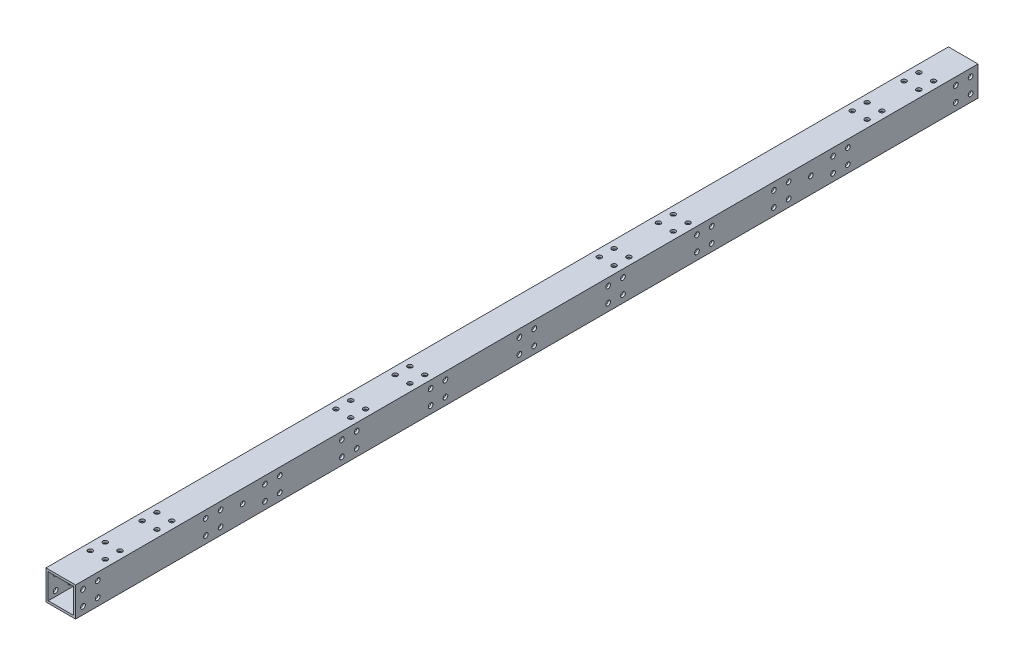
SolidWorks part; units mm, degrees
ref_plane "前视基准面" through (0, 0, 0) normal (0, 0, 1) x (1, 0, 0)
ref_plane "上视基准面" through (0, 0, 0) normal (0, 1, 0) x (1, 0, 0)
ref_plane "右视基准面" through (0, 0, 0) normal (1, 0, 0) x (0, 0, -1)
other "Configuration Table"
sketch "草图1" plane through (0, 0, 0) normal (0, 0, 1) x (1, 0, 0)
  line L10 (0, 0) -> (20, 0)
  line L11 (0, 0) -> (0, -20)
  line L12 (0, -20) -> (20, -20)
  line L13 (20, 0) -> (20, -20)
  dimension "D1" = 20
  dimension "D2" = 20
extrude "拉伸-薄壁1" add sketch "草图1" along normal blind 610 thin
sketch "草图2" plane through (0, 0, 0) normal (0, 1, 0) x (1, 0, 0)
  line L0 (20, -236) -> (0, -236) construction
  line L1 (20, -610) -> (20, 0) construction
  line L2 (0, -610) -> (0, 0) construction
  line L3 (20, 0) -> (0, 0) construction
  line L4 (0, -305) -> (20, -305) construction
  line L5 (10, -305) -> (10, -236) construction
  line L6 (20, -374) -> (0, -374) construction
  line L7 (0, -30) -> (20, -30) construction
  line L8 (0, -580) -> (20, -580) construction
  line L9 (0, -65) -> (20, -65) construction
  line L10 (0, -216) -> (20, -216) construction
  line L11 (20, -196) -> (0, -196) construction
  line L12 (0, -394) -> (20, -394) construction
  line L13 (20, -414) -> (0, -414) construction
  circle A0 centre (5, -231) radius 1.575
  circle A1 centre (15, -231) radius 1.575
  circle A2 centre (15, -241) radius 1.575
  circle A3 centre (5, -241) radius 1.575
  circle A4 centre (5, -369) radius 1.575
  circle A5 centre (15, -369) radius 1.575
  circle A6 centre (15, -379) radius 1.575
  circle A7 centre (5, -379) radius 1.575
  circle A8 centre (5, -25) radius 1.575
  circle A9 centre (15, -25) radius 1.575
  circle A10 centre (15, -35) radius 1.575
  circle A11 centre (5, -35) radius 1.575
  circle A12 centre (5, -575) radius 1.575
  circle A13 centre (15, -575) radius 1.575
  circle A14 centre (15, -585) radius 1.575
  circle A15 centre (5, -585) radius 1.575
  circle A16 centre (5, -60) radius 1.575
  circle A17 centre (15, -60) radius 1.575
  circle A18 centre (15, -70) radius 1.575
  circle A19 centre (5, -70) radius 1.575
  circle A20 centre (5, -540) radius 1.575
  circle A21 centre (15, -540) radius 1.575
  circle A22 centre (15, -550) radius 1.575
  circle A23 centre (5, -550) radius 1.575
  circle A24 centre (5, -191) radius 1.575
  circle A25 centre (15, -191) radius 1.575
  circle A26 centre (15, -201) radius 1.575
  circle A27 centre (5, -201) radius 1.575
  circle A28 centre (5, -409) radius 1.575
  circle A29 centre (15, -409) radius 1.575
  circle A30 centre (15, -419) radius 1.575
  circle A31 centre (5, -419) radius 1.575
  dimension "D2" = 3.15
  dimension "D6" = 3.15
  dimension "D10" = 3.15
  dimension "D1" = 236
  dimension "D3" = 5
  dimension "D4" = 5
  dimension "D5" = 30
  dimension "D7" = 5
  dimension "D8" = 5
  dimension "D9" = 240
  dimension "D11" = 5
  dimension "D12" = 5
  dimension "D13" = 216
extrude "切除-拉伸1" cut sketch "草图2" against normal through all
sketch "草图3" plane through (0, 0, 0) normal (-1, 0, 0) x (0, 0, 1)
  line L0 (305, 0) -> (305, -20) construction
  line L1 (610, 0) -> (0, 0) construction
  line L2 (610, -20) -> (0, -20) construction
  line L3 (0, 0) -> (0, -20) construction
  line L4 (93, 0) -> (93, -20) construction
  line L5 (93, -10) -> (0, -10) construction
  line L6 (113, 0) -> (113, -20) construction
  line L7 (517, 0) -> (517, -20) construction
  line L8 (133, 0) -> (133, -20) construction
  line L9 (10, 0) -> (10, -10) construction
  line L10 (600, 0) -> (600, -10) construction
  circle A0 centre (113, -9) radius 1.575
  circle A1 centre (497, -9) radius 1.575
  circle A2 centre (88, -5) radius 1.575
  circle A3 centre (88, -15) radius 1.575
  circle A4 centre (98, -15) radius 1.575
  circle A5 centre (98, -5) radius 1.575
  circle A18 centre (512, -5) radius 1.575
  circle A19 centre (512, -15) radius 1.575
  circle A20 centre (522, -15) radius 1.575
  circle A21 centre (522, -5) radius 1.575
  circle A22 centre (128, -5) radius 1.575
  circle A23 centre (128, -15) radius 1.575
  circle A24 centre (138, -15) radius 1.575
  circle A25 centre (138, -5) radius 1.575
  circle A26 centre (472, -5) radius 1.575
  circle A27 centre (472, -15) radius 1.575
  circle A28 centre (482, -15) radius 1.575
  circle A29 centre (482, -5) radius 1.575
  circle A30 centre (300, -5) radius 1.6
  circle A31 centre (300, -15) radius 1.6
  circle A32 centre (310, -15) radius 1.6
  circle A33 centre (310, -5) radius 1.6
  circle A34 centre (250, -5) radius 1.6
  circle A35 centre (240, -5) radius 1.6
  circle A36 centre (240, -15) radius 1.6
  circle A37 centre (250, -15) radius 1.6
  circle A38 centre (190, -5) radius 1.6
  circle A39 centre (180, -5) radius 1.6
  circle A40 centre (180, -15) radius 1.6
  circle A41 centre (190, -15) radius 1.6
  circle A42 centre (420, -15) radius 1.6
  circle A43 centre (430, -15) radius 1.6
  circle A44 centre (430, -5) radius 1.6
  circle A45 centre (420, -5) radius 1.6
  circle A46 centre (360, -15) radius 1.6
  circle A47 centre (370, -15) radius 1.6
  circle A48 centre (370, -5) radius 1.6
  circle A49 centre (360, -5) radius 1.6
  circle A50 centre (5, -5) radius 1.6
  circle A51 centre (5, -15) radius 1.6
  circle A52 centre (15, -15) radius 1.6
  circle A53 centre (15, -5) radius 1.6
  circle A54 centre (595, -5) radius 1.6
  circle A55 centre (595, -15) radius 1.6
  circle A56 centre (605, -15) radius 1.6
  circle A57 centre (605, -5) radius 1.6
  dimension "D2" = 3.15
  dimension "D3" = 113
  dimension "D5" = 3.15
  dimension "D8" = 3.15
  dimension "D12" = 3.2
  dimension "D16" = 3.2
  dimension "D1" = 11
  dimension "D4" = 20
  dimension "D6" = 5
  dimension "D7" = 5
  dimension "D9" = 5
  dimension "D10" = 5
  dimension "D11" = 20
  dimension "D13" = 5
  dimension "D14" = 5
  dimension "D15" = 50
  dimension "D17" = 5
  dimension "D18" = 5
  dimension "D19" = 10
extrude "切除-拉伸2" cut sketch "草图3" against normal through all
